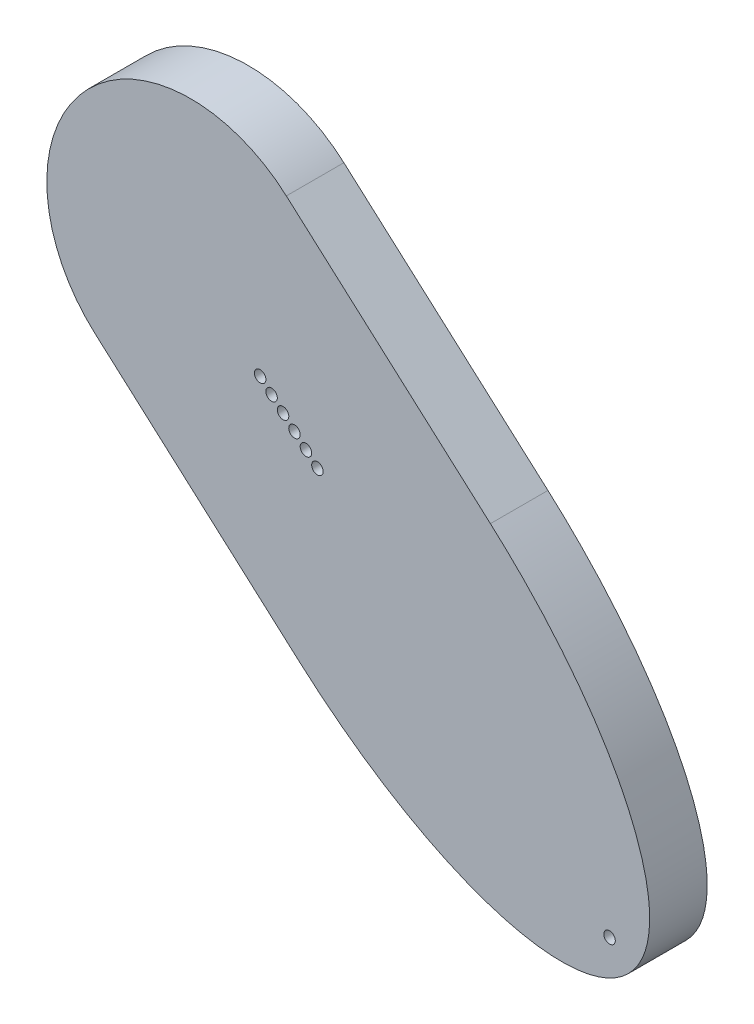
SolidWorks part; units mm, degrees
ref_plane "Plan de face" through (0, 0, 0) normal (0, 0, 1) x (1, 0, 0)
ref_plane "Plan de dessus" through (0, 0, 0) normal (0, 1, 0) x (1, 0, 0)
ref_plane "Plan de droite" through (0, 0, 0) normal (1, 0, 0) x (0, 0, -1)
sketch "Esquisse1" plane through (0, 0, 0) normal (0, 0, 1) x (1, 0, 0)
  line L0 (1.6629, 1.8668) -> (-1.6629, -1.8668)
  line L1 (-1.6629, -1.8668) -> (71.142, -66.7182)
  line L2 (71.142, -66.7182) -> (74.4677, -62.9846)
  line L3 (74.4677, -62.9846) -> (1.6629, 1.8668)
  line L4 (0, 0) -> (72.8049, -64.8514) construction
  line L5 (0, 0) -> (35.469, -31.5943) construction
  line L6 (16.6286, 18.6679) -> (52.0976, -12.9263)
  line L7 (-16.6286, -18.6679) -> (18.8405, -50.2622)
  line L8 (72.8049, -64.8514) -> (76.5385, -68.1771) construction
  line L10 (52.0976, -12.9263) -> (16.6286, 18.6679)
  line L11 (-16.6286, -18.6679) -> (18.8405, -50.2622)
  arc A0 (16.6286, 18.6679) -> (-16.6286, -18.6679) centre (0, 0) ccw
  circle A1 centre (0, 0) radius 5
  circle A2 centre (72.8049, -64.8514) radius 5
  circle A3 centre (72.8049, -64.8514) radius 1
  circle A4 centre (0, 0) radius 1
  arc A5 (18.8405, -50.2622) -> (52.0976, -12.9263) centre (35.469, -31.5943) ccw
  circle A6 centre (0, 0) radius 25
  ellipse E0 centre (35.469, -31.5943) end of major axis (76.5385, -68.1771) minor radius 25
  point P2 (0, 0)
  point P8 (72.8049, -64.8514)
  point P16 (17.7345, -15.7971)
  point P22 (54.137, -48.2228)
  dimension "D2" = 2
  dimension "D3" = 10
  dimension "D4" = 10
  dimension "D5" = 2
  dimension "D1" = 5
  dimension "D6" = 50
  dimension "D7" = 25
  dimension "D8" = 47.5
extrude "Boss.-Extru.1" add sketch "Esquisse1" against normal blind 10 from offset 10 contours A4 L0 L3 A1 L1 | A4 L0 L1 A1 L3 | A2 L3 A1 L1 | A3 L2 L1 A2 L3 | A3 L2 L3 A2 L1 | E0 | L7 A5 L6 A0 offset against normal yes
sketch "Esquisse2" plane through (0, 0, -20) normal (0, 0, -1) x (-1, 0, 0)
  line L0 (0, 0) -> (-20.5347, -18.2914)
  line L1 (-72.8049, -64.8514) -> (0, 0)
  line L2 (-23.5278, -14.9312) -> (-17.5416, -21.6516)
  line L3 (-4.656, 5.227) -> (4.656, -5.227)
  line L4 (-23.5278, -14.9312) -> (-4.656, 5.227)
  line L5 (4.656, -5.227) -> (-17.5416, -21.6516)
  line L6 (-30.5118, -7.0907) -> (-9.9771, 11.2007)
  line L7 (-30.5118, -7.0907) -> (-10.5576, -29.4922)
  line L9 (-10.5576, -29.4922) -> (9.9771, -11.2007)
  line L10 (9.9771, -11.2007) -> (-10.5576, -29.4922)
  line L11 (-9.9771, 11.2007) -> (9.9771, -11.2007)
  line L12 (-17.5416, -21.6516) -> (-10.5576, -29.4922)
  line L13 (4.656, -5.227) -> (9.9771, -11.2007)
  line L14 (-4.656, 5.227) -> (-9.9771, 11.2007)
  line L15 (-23.5278, -14.9312) -> (-30.5118, -7.0907)
  circle A0 centre (0, 0) radius 7
  circle A1 centre (-20.5347, -18.2914) radius 4.5
  circle A2 centre (0, 0) radius 15
  circle A3 centre (-20.5347, -18.2914) radius 15
  dimension "D1" = 14
  dimension "D2" = 9
  dimension "D4" = 30
  dimension "D5" = 30
  dimension "D3" = 27.5
extrude "Boss.-Extru.4" add sketch "Esquisse2" along normal blind 4 contours L7 A3 L1 A1 | L1 A3 L7 A1 | A2 A3 L7 L4 | L7 A3 A2 L5 | A3 L4 A0 L11 A2 | L11 A2 A0 | A3 A2 L11 A0 L5 | A3 L9 A2 | A3 A2 L6
sketch "Esquisse3" plane through (0, 0, -20) normal (0, 0, -1) x (-1, 0, 0)
  line L0 (-23.8949, -21.2846) -> (-22.0281, -19.6217) construction
  line L1 (0, 0) -> (-72.8049, -64.8514) construction
  line L2 (-22.0281, -19.6217) -> (-20.0369, -17.848) construction
  line L3 (-20.0369, -17.848) -> (-18.0456, -16.0742) construction
  line L4 (-18.0456, -16.0742) -> (-16.0543, -14.3005) construction
  line L5 (-16.0543, -14.3005) -> (-14.0631, -12.5268) construction
  line L6 (-14.0631, -12.5268) -> (-12.0718, -10.753) construction
  arc A0 (-23.5278, -14.9312) -> (-17.5416, -21.6516) centre (-20.5347, -18.2914) ccw construction
  circle A1 centre (-20.0369, -17.848) radius 1
  circle A2 centre (-22.0281, -19.6217) radius 1
  circle A3 centre (-18.0456, -16.0742) radius 1
  circle A4 centre (-16.0543, -14.3005) radius 1
  circle A5 centre (-14.0631, -12.5268) radius 1
  circle A6 centre (-12.0718, -10.753) radius 1
  dimension "D3" = 2
  dimension "D4" = 2
  dimension "D5" = 2
  dimension "D6" = 2
  dimension "D7" = 2
  dimension "D8" = 2
  dimension "D1" = 2.6667
  dimension "D2" = 2.5
extrude "Enlèv. mat.-Extru.1" cut sketch "Esquisse3" against normal through all
